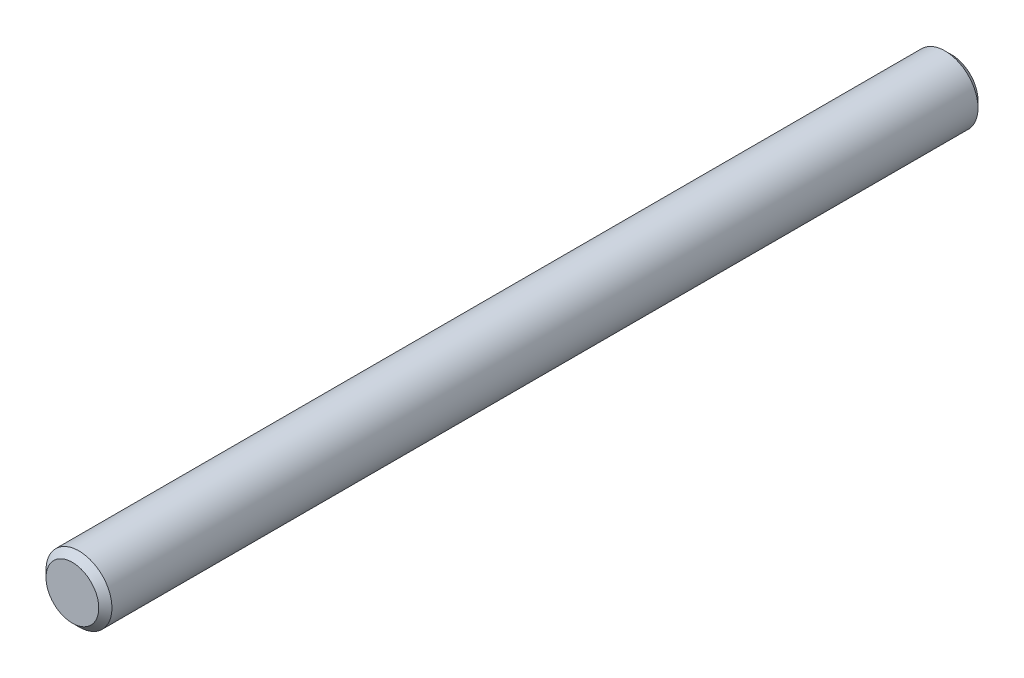
SolidWorks part; units mm, degrees
material "Простая углеродистая сталь"
ref_plane "Front" through (0, 0, 0) normal (0, 0, 1) x (1, 0, 0)
ref_plane "Top" through (0, 0, 0) normal (0, 1, 0) x (1, 0, 0)
ref_plane "Right" through (0, 0, 0) normal (1, 0, 0) x (0, 0, -1)
sketch "Эскиз1" plane through (0, 0, 0) normal (0, 0, 1) x (1, 0, 0)
  circle A0 centre (0, 0) radius 1.5
  dimension "D1" = 3
extrude "Бобышка-Вытянуть1" add sketch "Эскиз1" along normal mid plane 40
chamfer "Фаска1" distance 0.3 angle 45 2 edges at (1.5, 0, -20) (1.5, 0, 20)
